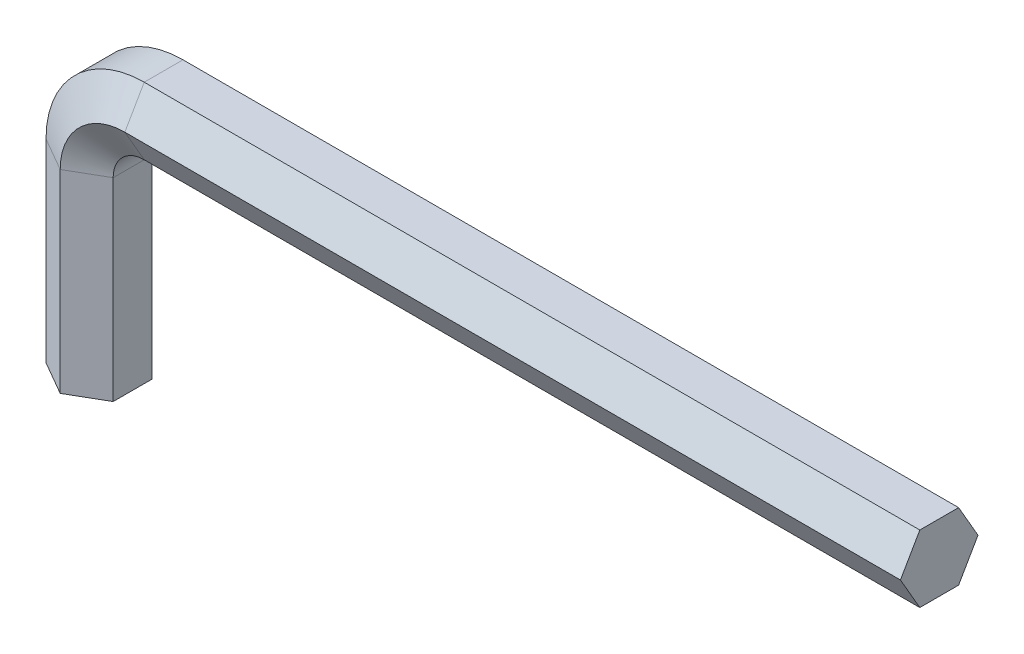
SolidWorks part; units mm, degrees
ref_plane "Front Plane" through (0, 0, 0) normal (0, 0, 1) x (1, 0, 0)
ref_plane "Top Plane" through (0, 0, 0) normal (0, 1, 0) x (1, 0, 0)
ref_plane "Right Plane" through (0, 0, 0) normal (1, 0, 0) x (0, 0, -1)
sketch "Sketch1" plane through (0, 0, 0) normal (0, 0, 1) x (1, 0, 0)
  line L0 (5, 0) -> (65, 0)
  line L1 (0, -5) -> (0, -20)
  arc A0 (5, 0) -> (0, -5) centre (5, -5) ccw
  point P6 (0, 0)
  dimension "D1" = 5
  dimension "D2" = 60
  dimension "D3" = 15
ref_plane "Plane1" through (0, -20, 0) normal (0, -1, 0) x (-1, 0, 0)
sketch "Sketch2" plane through (0, -20, 0) normal (0, -1, 0) x (-1, 0, 0)
  line L1 (0, 3) -> (-2.5981, 1.5)
  line L2 (-2.5981, 1.5) -> (-2.5981, -1.5)
  line L3 (-2.5981, -1.5) -> (0, -3)
  line L4 (0, -3) -> (2.5981, -1.5)
  line L5 (2.5981, -1.5) -> (2.5981, 1.5)
  line L6 (2.5981, 1.5) -> (0, 3)
  circle A0 centre (0, 0) radius 2.5981 construction
  dimension "D1" = 3
sweep "Sweep1" add profiles "Sketch2" path "Sketch1"
